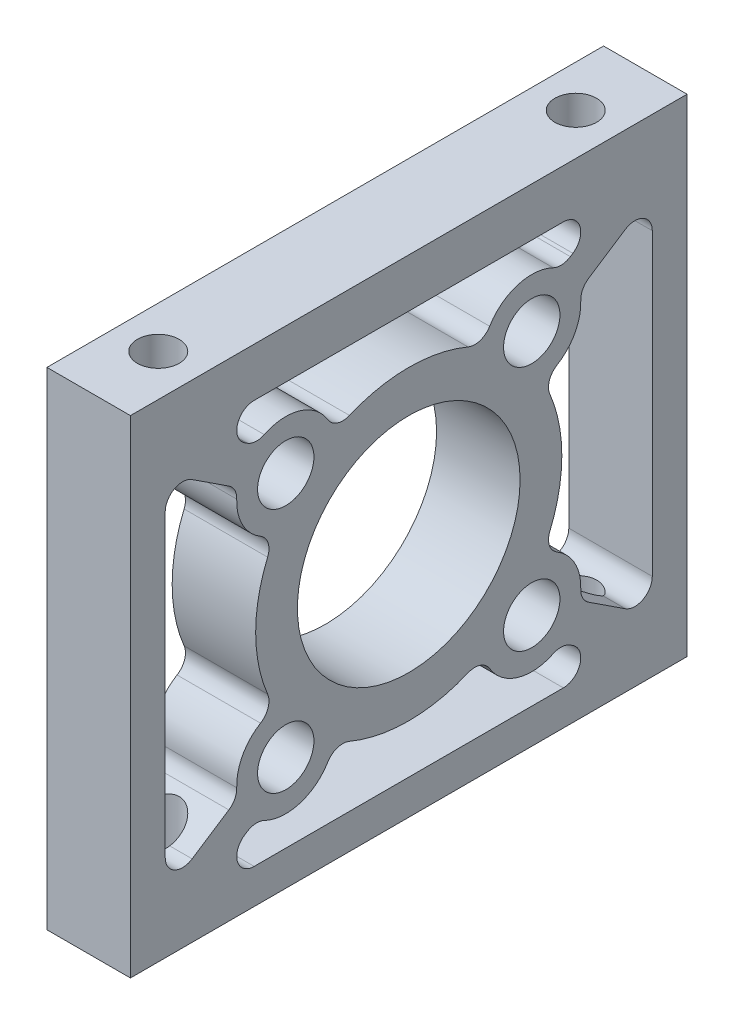
SolidWorks part; units mm, degrees
material "6061 合金"
ref_plane "前视基准面" through (0, 0, 0) normal (0, 0, 1) x (1, 0, 0)
ref_plane "上视基准面" through (0, 0, 0) normal (0, 1, 0) x (1, 0, 0)
ref_plane "右视基准面" through (0, 0, 0) normal (1, 0, 0) x (0, 0, -1)
sketch "草图1" plane through (0, 0, 0) normal (1, 0, 0) x (0, 0, -1)
  line L1 (-17, 17) -> (17, 17) construction
  line L2 (-17, 17) -> (-17, -17) construction
  line L3 (-17, -17) -> (17, -17) construction
  line L4 (17, 17) -> (17, -17) construction
  line L5 (-17, 17) -> (17, -17) construction
  line L6 (-17, -17) -> (17, 17) construction
  line L7 (-20, 17) -> (20, 17)
  line L8 (-20, 17) -> (-20, -17)
  line L9 (-20, -17) -> (20, -17)
  line L10 (20, 17) -> (20, -17)
  line L11 (-20, 17) -> (20, -17) construction
  line L12 (-20, -17) -> (20, 17) construction
  circle A0 centre (0, 0) radius 12.5 construction
  circle A1 centre (-8.8388, 8.8388) radius 2.025
  circle A2 centre (8.8388, 8.8388) radius 2.025
  circle A3 centre (8.8388, -8.8388) radius 2.025
  circle A4 centre (-8.8388, -8.8388) radius 2.025
  circle A5 centre (0, 0) radius 7
  point P0 (0, 0)
  dimension "D1" = 25
  dimension "D2" = 4.05
  dimension "D3" = 17
  dimension "D4" = 14
  dimension "D5" = 40
extrude "凸台-拉伸1" add sketch "草图1" along normal blind 6
sketch "草图2" plane through (6, 0, 0) normal (1, 0, 0) x (0, 0, -1)
  line L0 (-17.5, 14.5) -> (-8.8388, 8.8388)
  line L1 (-17.5, -14.5) -> (-8.8388, -8.8388)
  line L2 (8.8388, 8.8388) -> (17.5, 14.5)
  line L4 (8.8388, -8.8388) -> (17.5, -14.5)
  line L5 (17.5, -14.5) -> (17.5, 14.5)
  line L6 (17.5, 14.5) -> (-17.5, 14.5)
  line L7 (-17.5, 14.5) -> (-17.5, -14.5)
  line L8 (-17.5, -14.5) -> (17.5, -14.5)
  line L9 (20, -17) -> (20, 17)
  line L10 (20, 17) -> (-20, 17)
  line L11 (-20, 17) -> (-20, -17)
  line L12 (-20, -17) -> (20, -17)
  line L13 (20, -17) -> (20, 17)
  line L14 (20, 17) -> (-20, 17)
  line L15 (-20, 17) -> (-20, -17)
  line L16 (-20, -17) -> (20, -17)
  line L17 (-18.1565, 13.4955) -> (-9.4954, 7.8344)
  line L18 (-16.8435, -15.5045) -> (-8.1823, -9.8433)
  line L19 (8.1823, -9.8433) -> (16.8435, -15.5045)
  line L20 (9.4954, 7.8344) -> (18.1565, 13.4955)
  line L21 (-16.8435, 15.5045) -> (-8.1823, 9.8433)
  line L22 (-18.1565, -13.4955) -> (-9.4954, -7.8344)
  line L23 (9.4954, -7.8344) -> (18.1565, -13.4955)
  line L24 (8.1823, 9.8433) -> (16.8435, 15.5045)
  circle A0 centre (-8.8388, -8.8388) radius 3.525
  circle A1 centre (-8.8388, 8.8388) radius 2.025
  circle A2 centre (-8.8388, 8.8388) radius 2.025
  circle A3 centre (8.8388, 8.8388) radius 2.025
  circle A4 centre (8.8388, 8.8388) radius 2.025
  circle A5 centre (8.8388, -8.8388) radius 2.025
  circle A6 centre (8.8388, -8.8388) radius 2.025
  circle A7 centre (-8.8388, -8.8388) radius 2.025
  circle A8 centre (-8.8388, -8.8388) radius 2.025
  circle A9 centre (0, 0) radius 7
  circle A10 centre (0, 0) radius 7
  circle A11 centre (8.8388, -8.8388) radius 3.525
  circle A12 centre (8.8388, 8.8388) radius 3.525
  circle A13 centre (-8.8388, 8.8388) radius 3.525
  circle A14 centre (0, 0) radius 11
  dimension "D1" = 0
  dimension "D2" = 0
  dimension "D3" = 0
  dimension "D4" = 0
  dimension "D5" = 0
  dimension "D6" = 0
  dimension "D7" = 2.5
  dimension "D8" = 1.5
  dimension "D9" = 4
  dimension "D10" = 1.2
  dimension "D11" = 1.2
extrude "切除-拉伸1" cut sketch "草图2" against normal blind 8 contours A14 A13 L17 L7 L22 A0 | A14 A12 L24 L6 L21 A13 | A14 A11 L23 L5 L20 A12 | A14 A0 L18 L8 L19 A11
fillet "圆角2" radius 1.25 24 edges at (3, 13.0664, -17.5) (3, 9.6478, -12.2698) (3, 5.3941, -9.5867) (3, 9.5867, -5.3941) (3, -5.3941, -9.5867) (3, -9.5867, -5.3941) (3, -9.6478, -12.2698) (3, -13.0664, -17.5) (3, -14.5, -15.3067) (3, -5.3941, 9.5867) (3, -9.5867, 5.3941) (3, -11.6567, -10.9567) (3, -11.6567, 10.9567) (3, -14.5, 15.3067) (3, -13.0664, 17.5) (3, 14.5, -15.3067) (3, 11.6567, -10.9567) (3, 5.3941, 9.5867) (3, 9.5867, 5.3941) (3, 11.6567, 10.9567) (3, 14.5, 15.3067) (3, 13.0664, 17.5) (3, -9.6478, 12.2698) (3, 9.6478, 12.2698)
sketch "草图4" plane through (0, 17, 0) normal (0, 1, 0) x (1, 0, 0)
  line L0 (3, 20) -> (3, -20) construction
  line L1 (6, 20) -> (0, 20) construction
  line L2 (6, -20) -> (0, -20) construction
  line L3 (6, 0) -> (0, 0) construction
  line L4 (6, 20) -> (6, -20) construction
  line L5 (0, 20) -> (0, -20) construction
  circle A0 centre (3, 15) radius 1.5
  circle A1 centre (3, -15) radius 1.5
  dimension "D1" = 3
  dimension "D2" = 5
extrude "切除-拉伸2" cut sketch "草图4" against normal through all
sketch "草图5" plane through (0, 17, 0) normal (0, 1, 0) x (1, 0, 0)
  line L4 (0, 20) -> (0, -20)
  line L5 (0, -20) -> (6, -20)
  line L6 (6, -20) -> (6, 20)
  line L7 (6, 20) -> (0, 20)
  line L8 (0, 20) -> (0, -20)
  line L9 (0, -20) -> (6, -20)
  line L10 (6, -20) -> (6, 20)
  line L11 (6, 20) -> (0, 20)
  circle A1 centre (3, -15) radius 1.5
  circle A2 centre (3, -15) radius 1.5
  circle A3 centre (3, 15) radius 1.5
  circle A4 centre (3, 15) radius 1.5
  dimension "D1" = 0
  dimension "D2" = 0
  dimension "D3" = 0
extrude "凸台-拉伸2" add sketch "草图5" along normal blind 1
sketch "草图6" plane through (6, 0, 0) normal (1, 0, 0) x (0, 0, -1)
  circle A0 centre (0, 0) radius 8
  circle A1 centre (0, 0) radius 7 construction
  dimension "D1" = 1
extrude "切除-拉伸3" cut sketch "草图6" against normal through all
